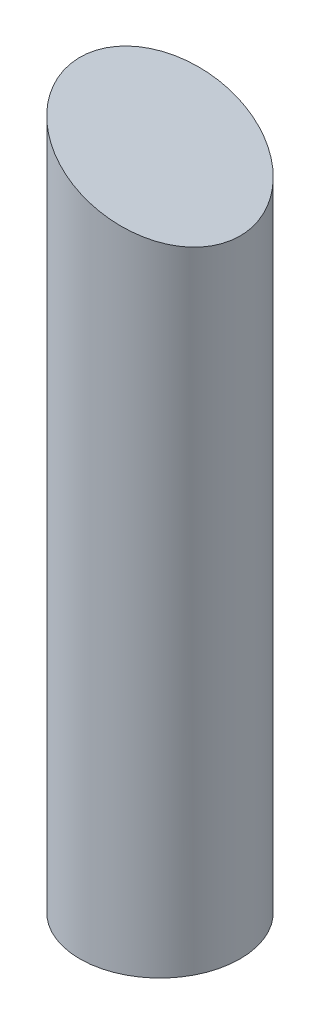
SolidWorks part; units mm, degrees
ref_plane "Alzado" through (0, 0, 0) normal (0, 0, 1) x (1, 0, 0)
ref_plane "Planta" through (0, 0, 0) normal (0, 1, 0) x (1, 0, 0)
ref_plane "Vista lateral" through (0, 0, 0) normal (1, 0, 0) x (0, 0, -1)
sketch "Croquis1" plane through (0, 0, 0) normal (0, 1, 0) x (1, 0, 0)
  circle A0 centre (0, 0) radius 4
  dimension "D1" = 8
extrude "Saliente-Extruir1" add sketch "Croquis1" along normal blind 35
ref_plane "Plano1" through (0, 0, 4) normal (0, 0, 1) x (1, 0, 0)
sketch "Croquis2" plane through (0, 0, 4) normal (0, 0, 1) x (1, 0, 0)
  line L0 (-4, 35) -> (4, 31.2695)
  line L1 (4, 0) -> (4, 35) construction
  line L2 (4, 31.2695) -> (4, 35)
  line L3 (4, 35) -> (-4, 35)
  dimension "D1" = 25
extrude "Cortar-Extruir1" cut sketch "Croquis2" against normal blind 10
